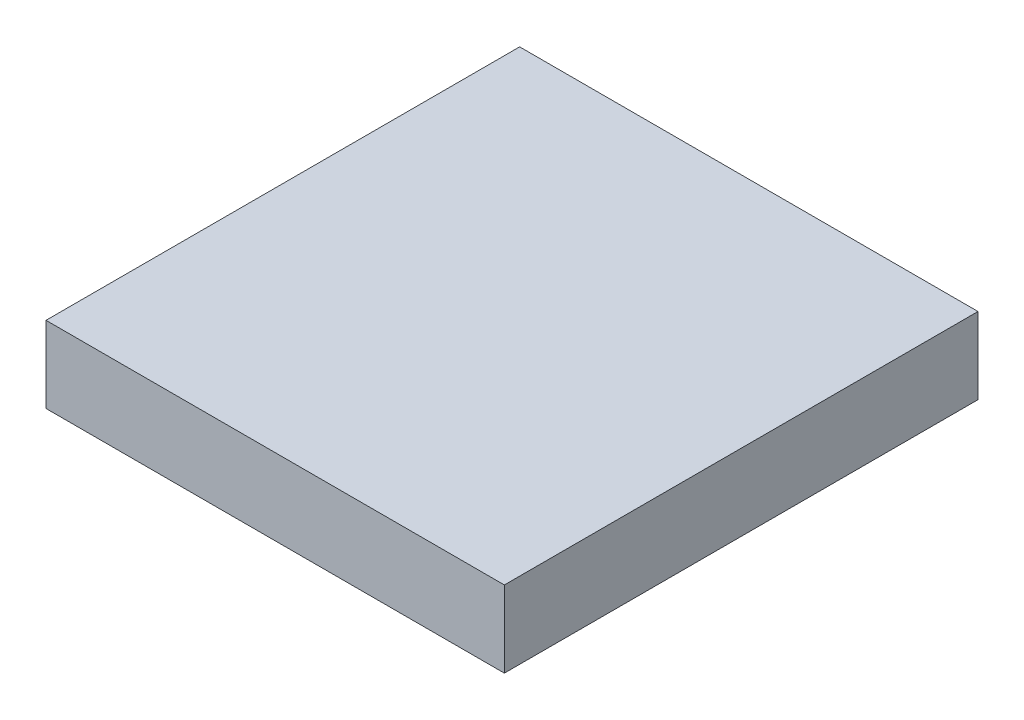
SolidWorks part; units mm, degrees
ref_plane "Front Plane" through (0, 0, 0) normal (0, 0, 1) x (1, 0, 0)
ref_plane "Top Plane" through (0, 0, 0) normal (0, 1, 0) x (1, 0, 0)
ref_plane "Right Plane" through (0, 0, 0) normal (1, 0, 0) x (0, 0, -1)
sketch "Sketch1" plane through (0, 0, 0) normal (0, 1, 0) x (1, 0, 0)
  line L1 (-19.05, 19.685) -> (19.05, 19.685)
  line L2 (-19.05, 19.685) -> (-19.05, -19.685)
  line L3 (-19.05, -19.685) -> (19.05, -19.685)
  line L4 (19.05, 19.685) -> (19.05, -19.685)
  line L5 (-19.05, 19.685) -> (19.05, -19.685) construction
  line L6 (-19.05, -19.685) -> (19.05, 19.685) construction
  point P0 (0, 0)
  dimension "D1" = 38.1
  dimension "D2" = 39.37
extrude "Boss-Extrude1" add sketch "Sketch1" along normal blind 6.35
